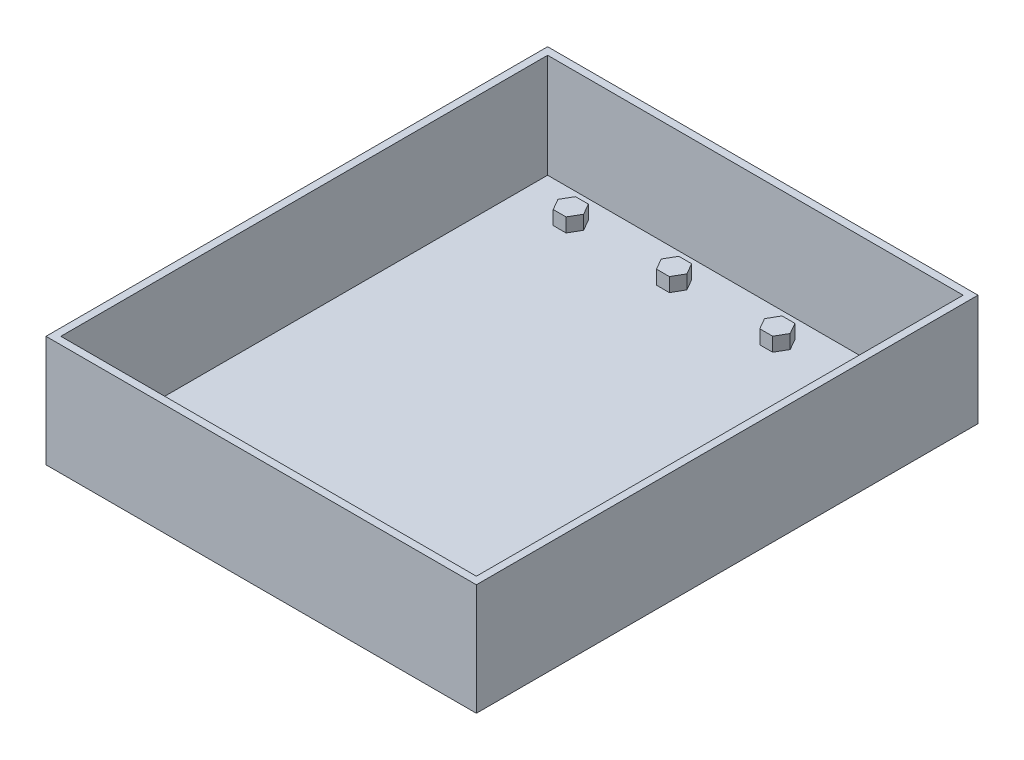
SolidWorks part; units mm, degrees
ref_plane "Front Plane" through (0, 0, 0) normal (0, 0, 1) x (1, 0, 0)
ref_plane "Top Plane" through (0, 0, 0) normal (0, 1, 0) x (1, 0, 0)
ref_plane "Right Plane" through (0, 0, 0) normal (1, 0, 0) x (0, 0, -1)
sketch "Sketch1" plane through (0, 0, 0) normal (0, 1, 0) x (1, 0, 0)
  line L1 (-92.075, 107.315) -> (92.075, 107.315)
  line L2 (-92.075, 107.315) -> (-92.075, -107.315)
  line L3 (-92.075, -107.315) -> (92.075, -107.315)
  line L4 (92.075, 107.315) -> (92.075, -107.315)
  line L5 (-92.075, 107.315) -> (92.075, -107.315) construction
  line L6 (-92.075, -107.315) -> (92.075, 107.315) construction
  point P0 (0, 0)
  dimension "D1" = 184.15
  dimension "D2" = 214.63
extrude "Boss-Extrude1" add sketch "Sketch1" along normal blind 47.625
shell "Shell1" thickness 3.175
sketch "Sketch3" plane through (0, 3.175, 0) normal (0, 1, 0) x (1, 0, 0)
  line L0 (-27.5973, -91.44) -> (-24.8476, -96.2025)
  line L1 (-71.7933, -91.44) -> (-69.0436, -96.2025)
  line L2 (-69.0436, -96.2025) -> (-63.5444, -96.2025)
  line L3 (-63.5444, -96.2025) -> (-60.7947, -91.44)
  line L4 (-60.7947, -91.44) -> (-63.5444, -86.6775)
  line L5 (-63.5444, -86.6775) -> (-69.0436, -86.6775)
  line L6 (-69.0436, -86.6775) -> (-71.7933, -91.44)
  line L7 (-24.8476, -96.2025) -> (-19.3484, -96.2025)
  line L8 (-19.3484, -96.2025) -> (-16.5987, -91.44)
  line L9 (-16.5987, -91.44) -> (-19.3484, -86.6775)
  line L10 (-19.3484, -86.6775) -> (-24.8476, -86.6775)
  line L11 (-24.8476, -86.6775) -> (-27.5973, -91.44)
  line L12 (16.5987, -91.44) -> (19.3484, -96.2025)
  line L13 (19.3484, -96.2025) -> (24.8476, -96.2025)
  line L14 (24.8476, -96.2025) -> (27.5973, -91.44)
  line L15 (27.5973, -91.44) -> (24.8476, -86.6775)
  line L16 (24.8476, -86.6775) -> (19.3484, -86.6775)
  line L17 (19.3484, -86.6775) -> (16.5987, -91.44)
  line L18 (60.7947, -91.44) -> (63.5444, -96.2025)
  line L19 (63.5444, -96.2025) -> (69.0436, -96.2025)
  line L20 (69.0436, -96.2025) -> (71.7933, -91.44)
  line L21 (71.7933, -91.44) -> (69.0436, -86.6775)
  line L22 (69.0436, -86.6775) -> (63.5444, -86.6775)
  line L23 (63.5444, -86.6775) -> (60.7947, -91.44)
  line L24 (-27.5973, 91.44) -> (-24.8476, 86.6775)
  line L25 (-24.8476, 86.6775) -> (-19.3484, 86.6775)
  line L26 (-19.3484, 86.6775) -> (-16.5987, 91.44)
  line L27 (-16.5987, 91.44) -> (-19.3484, 96.2025)
  line L28 (-19.3484, 96.2025) -> (-24.8476, 96.2025)
  line L29 (-24.8476, 96.2025) -> (-27.5973, 91.44)
  line L30 (16.5987, 91.44) -> (19.3484, 86.6775)
  line L31 (19.3484, 86.6775) -> (24.8476, 86.6775)
  line L32 (24.8476, 86.6775) -> (27.5973, 91.44)
  line L33 (27.5973, 91.44) -> (24.8476, 96.2025)
  line L34 (24.8476, 96.2025) -> (19.3484, 96.2025)
  line L35 (19.3484, 96.2025) -> (16.5987, 91.44)
  line L36 (60.7947, 91.44) -> (63.5444, 86.6775)
  line L37 (63.5444, 86.6775) -> (69.0436, 86.6775)
  line L38 (69.0436, 86.6775) -> (71.7933, 91.44)
  line L39 (71.7933, 91.44) -> (69.0436, 96.2025)
  line L40 (69.0436, 96.2025) -> (63.5444, 96.2025)
  line L41 (63.5444, 96.2025) -> (60.7947, 91.44)
  line L42 (-71.7933, 91.44) -> (-69.0436, 86.6775)
  line L43 (-69.0436, 86.6775) -> (-63.5444, 86.6775)
  line L44 (-63.5444, 86.6775) -> (-60.7947, 91.44)
  line L45 (-60.7947, 91.44) -> (-63.5444, 96.2025)
  line L46 (-63.5444, 96.2025) -> (-69.0436, 96.2025)
  line L47 (-69.0436, 96.2025) -> (-71.7933, 91.44)
  line L48 (66.294, 91.44) -> (-66.294, -91.44) construction
  circle A0 centre (-66.294, -91.44) radius 4.7625 construction
  circle A1 centre (-22.098, -91.44) radius 4.7625 construction
  circle A2 centre (22.098, -91.44) radius 4.7625 construction
  circle A3 centre (66.294, -91.44) radius 4.7625 construction
  circle A4 centre (-22.098, 91.44) radius 4.7625 construction
  circle A5 centre (22.098, 91.44) radius 4.7625 construction
  circle A6 centre (66.294, 91.44) radius 4.7625 construction
  circle A7 centre (-66.294, 91.44) radius 4.7625 construction
  point P1 (0, 0)
  point P10 (0, 0)
  point P67 (-71.5393, -87.0593)
  point P68 (0, 0)
  point P69 (0, 0)
  point P70 (66.294, -91.44)
  point P71 (60.7947, -91.44)
  point P72 (0, 0)
  dimension "D1" = 9.525
  dimension "D4" = 44.196
  dimension "D5" = 182.88
  dimension "D2" = 4
  dimension "D3" = 2
extrude "Boss-Extrude2" add sketch "Sketch3" along normal blind 5.9531
